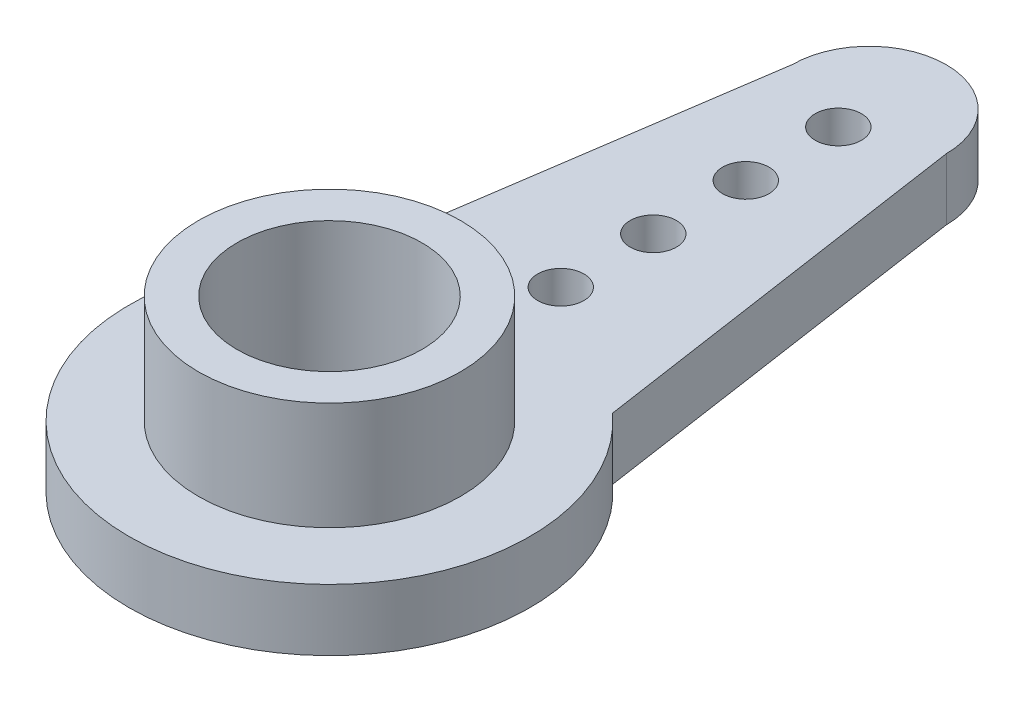
SolidWorks part; units mm, degrees
ref_plane "Vorne" through (0, 0, 0) normal (0, 0, 1) x (1, 0, 0)
ref_plane "Oben" through (0, 0, 0) normal (0, 1, 0) x (1, 0, 0)
ref_plane "Rechts" through (0, 0, 0) normal (1, 0, 0) x (0, 0, -1)
sketch "Skizze1" plane through (0, 0, 0) normal (0, 1, 0) x (1, 0, 0)
  line L0 (-2.5, 17.5) -> (-4.375, 4.8073)
  line L1 (2.5, 17.5) -> (4.375, 4.8073)
  arc A0 (-4.375, 4.8073) -> (4.375, 4.8073) centre (0, 0) ccw
  arc A1 (2.5, 17.5) -> (-2.5, 17.5) centre (0, 17.5) ccw
  point P3 (0, 20)
  dimension "D1" = 13
  dimension "D3" = 5
  dimension "D4" = 17.5
  dimension "D2" = 20
extrude "Aufsatz-Linear austragen1" add sketch "Skizze1" along normal blind 2
sketch "Skizze2" plane through (0, 2, 0) normal (0, 1, 0) x (1, 0, 0)
  circle A0 centre (0, 0) radius 4.25
  circle A1 centre (0, 0) radius 3
  dimension "D1" = 8.5
  dimension "D2" = 6
extrude "Aufsatz-Linear austragen2" add sketch "Skizze2" along normal blind 3.5
sketch "Skizze3" plane through (0, 2, 0) normal (0, 1, 0) x (1, 0, 0)
  circle A0 centre (0, 0) radius 3
extrude "Schnitt-Linear austragen1" cut sketch "Skizze3" against normal blind 3.5
sketch "Skizze4" plane through (0, 2, 0) normal (0, 1, 0) x (1, 0, 0)
  circle A0 centre (0, 7.5) radius 0.75
  circle A1 centre (0, 0) radius 3 construction
  circle A2 centre (0, 10.5) radius 0.75
  circle A3 centre (0, 13.5) radius 0.75
  circle A4 centre (0, 16.5) radius 0.75
  dimension "D1" = 7.5
  dimension "D2" = 1.5
  dimension "D3" = 3
  dimension "D4" = 3
  dimension "D5" = 3
  dimension "D6" = 1.5
  dimension "D7" = 1.5
  dimension "D8" = 1.5
extrude "Schnitt-Linear austragen2" cut sketch "Skizze4" against normal blind 3.5
